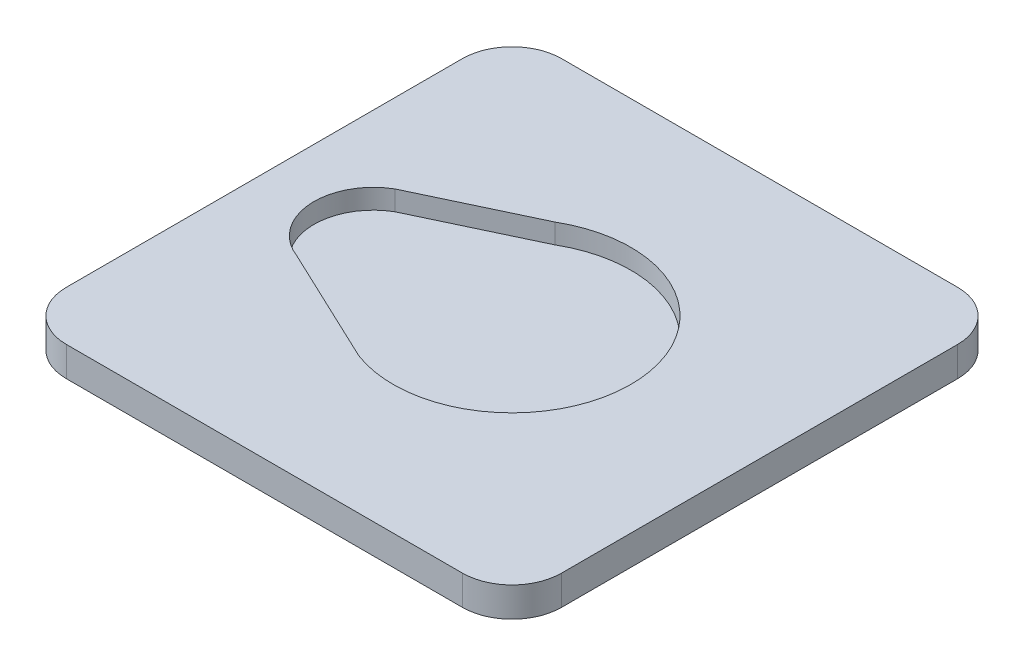
SolidWorks part; units mm, degrees
ref_plane "Front Plane" through (0, 0, 0) normal (0, 0, 1) x (1, 0, 0)
ref_plane "Top Plane" through (0, 0, 0) normal (0, 1, 0) x (1, 0, 0)
ref_plane "Right Plane" through (0, 0, 0) normal (1, 0, 0) x (0, 0, -1)
sketch "Sketch1" plane through (0, 0, 0) normal (0, 1, 0) x (1, 0, 0)
  line L1 (-100, 125) -> (100, 125)
  line L2 (-125, 100) -> (-125, -100)
  line L3 (-100, -125) -> (100, -125)
  line L4 (125, 100) -> (125, -100)
  line L5 (-125, 125) -> (125, -125) construction
  line L6 (-125, -125) -> (125, 125) construction
  line L8 (-70, 0) -> (0, 0) construction
  line L10 (-30.0806, 51.9149) -> (-85.0403, 25.9575)
  line L11 (-80.5871, -28.0698) -> (-21.1742, -56.1396)
  arc A0 (100, -125) -> (125, -100) centre (100, -100) ccw
  arc A1 (-125, -100) -> (-100, -125) centre (-100, -100) ccw
  arc A2 (100, 125) -> (125, 100) centre (100, 100) cw
  arc A3 (-125, 100) -> (-100, 125) centre (-100, 100) cw
  circle A4 centre (0, 0) radius 40 construction
  arc A10 (-21.1742, -56.1396) -> (-30.0806, 51.9149) centre (0, 0) ccw
  arc A11 (-85.0403, 25.9575) -> (-80.5871, -28.0698) centre (-70, 0) ccw
  point P0 (0, 0)
  dimension "D2" = 25
  dimension "D3" = 80
  dimension "D4" = 30
  dimension "D5" = 60
  dimension "D1" = 250
  dimension "D6" = 70
extrude "Boss-Extrude1" add sketch "Sketch1" along normal blind 15
sketch "Sketch2" plane through (0, 0, 0) normal (0, -1, 0) x (1, 0, 0)
  line L4 (100, 125) -> (-100, 125)
  line L5 (-125, 100) -> (-125, -100)
  line L6 (-100, -125) -> (100, -125)
  line L7 (125, -100) -> (125, 100)
  line L8 (100, 125) -> (-100, 125)
  line L9 (-125, 100) -> (-125, -100)
  line L10 (-100, -125) -> (100, -125)
  line L11 (125, -100) -> (125, 100)
  arc A4 (125, 100) -> (100, 125) centre (100, 100) ccw
  arc A5 (-100, 125) -> (-125, 100) centre (-100, 100) ccw
  arc A6 (-125, -100) -> (-100, -125) centre (-100, -100) ccw
  arc A7 (100, -125) -> (125, -100) centre (100, -100) ccw
  arc A8 (125, 100) -> (100, 125) centre (100, 100) ccw
  arc A9 (-100, 125) -> (-125, 100) centre (-100, 100) ccw
  arc A10 (-125, -100) -> (-100, -125) centre (-100, -100) ccw
  arc A11 (100, -125) -> (125, -100) centre (100, -100) ccw
  dimension "D1" = 0
extrude "Boss-Extrude2" add sketch "Sketch2" against normal blind 5
sketch "Sketch3" plane through (0, 0, 0) normal (0, 0, 1) x (1, 0, 0)
  line L0 (0, 5) -> (0, 155) construction
  line L1 (60, 5) -> (-30.0806, 5) construction
  line L2 (0, 31.4764) -> (0, -21.9177) construction
  spline S0 degree 3 poles (0, 5) (0, 164.2434) (-20.4307, 280.0158) (231.1861, 371.1573) knots 0 0 0 0 1 1 1 1
  dimension "D1" = 150
sketch "Sketch4" plane through (0, 0, 0) normal (0, -1, 0) x (1, 0, 0)
  line L8 (100, 100) -> (-100, 100)
  line L9 (-100, 100) -> (-100, -100)
  line L10 (-100, -100) -> (100, -100)
  line L11 (100, -100) -> (100, 100)
  line L12 (100, 100) -> (-100, 100)
  line L13 (-100, 100) -> (-100, -100)
  line L14 (-100, -100) -> (100, -100)
  line L15 (100, -100) -> (100, 100)
  dimension "D1" = 25
extrude "Cut-Extrude1" cut sketch "Sketch4" against normal blind 1
